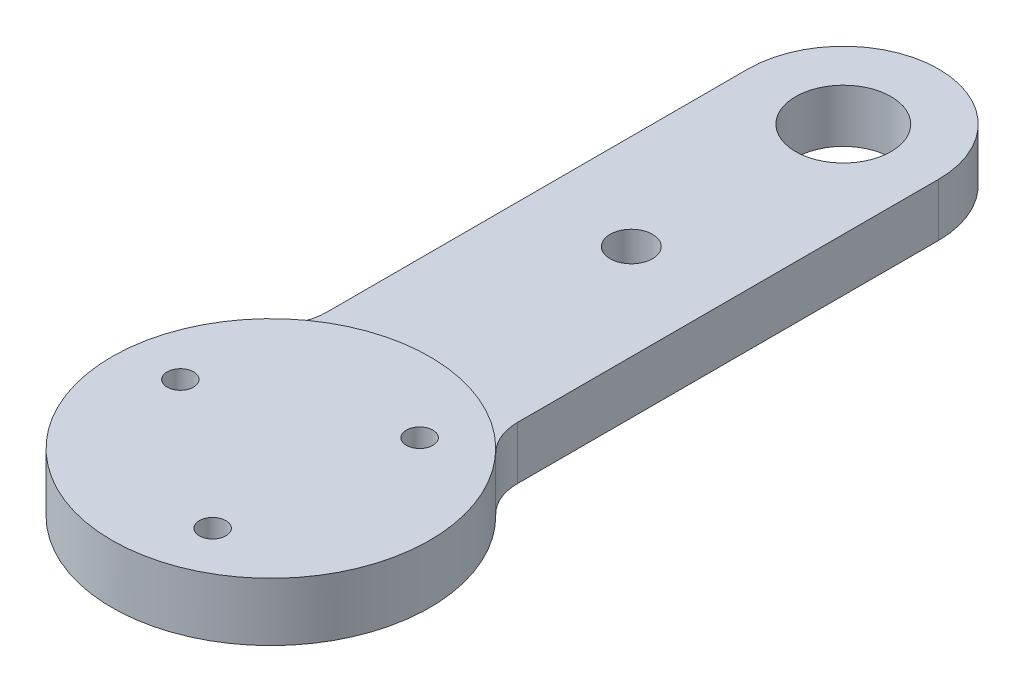
SolidWorks part; units mm, degrees
ref_plane "前视基准面" through (0, 0, 0) normal (0, 0, 1) x (1, 0, 0)
ref_plane "上视基准面" through (0, 0, 0) normal (0, 1, 0) x (1, 0, 0)
ref_plane "右视基准面" through (0, 0, 0) normal (1, 0, 0) x (0, 0, -1)
sketch "草图1" plane through (0, 0, 0) normal (0, 1, 0) x (1, 0, 0)
  line L0 (-14.8605, 23.5465) -> (-14.8605, -16.1706)
  line L3 (3.1395, 23.5465) -> (3.1395, 3.5465)
  line L4 (3.1395, 3.5465) -> (3.1395, -16.1706)
  arc A0 (3.1395, 23.5465) -> (-14.8605, 23.5465) centre (-5.8605, 23.5465) ccw
  circle A1 centre (-5.8605, 23.5465) radius 4.5
  circle A2 centre (-5.8605, 3.5465) radius 2
  arc A3 (-16.3605, -19.7413) -> (4.6395, -19.7413) centre (-5.8605, -30.4535) ccw
  circle A5 centre (-5.8605, -30.4535) radius 4.5
  circle A6 centre (-15.7665, -29.086) radius 1.25
  circle A7 centre (-2.0918, -39.7161) radius 1.25
  circle A8 centre (0.2769, -22.5584) radius 1.25
  arc A9 (-16.3605, -19.7413) -> (-14.8605, -16.1706) centre (-19.8605, -16.1706) ccw
  arc A10 (4.6395, -19.7413) -> (3.1395, -16.1706) centre (8.1395, -16.1706) cw
  dimension "D5" = 5
  dimension "D1" = 5
  dimension "D3" = 9
  dimension "D4" = 20
extrude "凸台-拉伸2" add sketch "草图1" along normal blind 0.5
sketch "草图2" plane through (0, 0.5, 0) normal (0, 1, 0) x (1, 0, 0)
  line L2 (-14.8605, 23.5465) -> (-14.8605, -16.1706)
  line L4 (3.1395, 23.5465) -> (3.1395, -16.1706)
  circle A0 centre (-5.8605, 23.5465) radius 4.5
  circle A1 centre (-5.8605, 3.5465) radius 2
  circle A2 centre (-15.7665, -29.086) radius 1.25
  circle A3 centre (-2.0918, -39.7161) radius 1.25
  circle A4 centre (0.2769, -22.5584) radius 1.25
  arc A5 (-14.8605, 23.5465) -> (3.1395, 23.5465) centre (-5.8605, 23.5465) cw
  arc A6 (-16.3605, -19.7413) -> (-14.8605, -16.1706) centre (-19.8605, -16.1706) ccw
  arc A7 (3.1395, -16.1706) -> (4.6395, -19.7413) centre (8.1395, -16.1706) ccw
  arc A8 (-16.3605, -19.7413) -> (4.6395, -19.7413) centre (-5.8605, -30.4535) ccw
extrude "凸台-拉伸3" add sketch "草图2" along normal blind 4.5
sketch "草图3" plane through (0, 5, 0) normal (0, 1, 0) x (1, 0, 0)
  circle A0 centre (-15.7665, -29.086) radius 1.25
  circle A1 centre (0.2769, -22.5584) radius 1.25
  circle A2 centre (-2.0918, -39.7161) radius 1.25
  circle A3 centre (-5.8605, -30.4535) radius 15
extrude "凸台-拉伸4" add sketch "草图3" along normal blind 0.5
